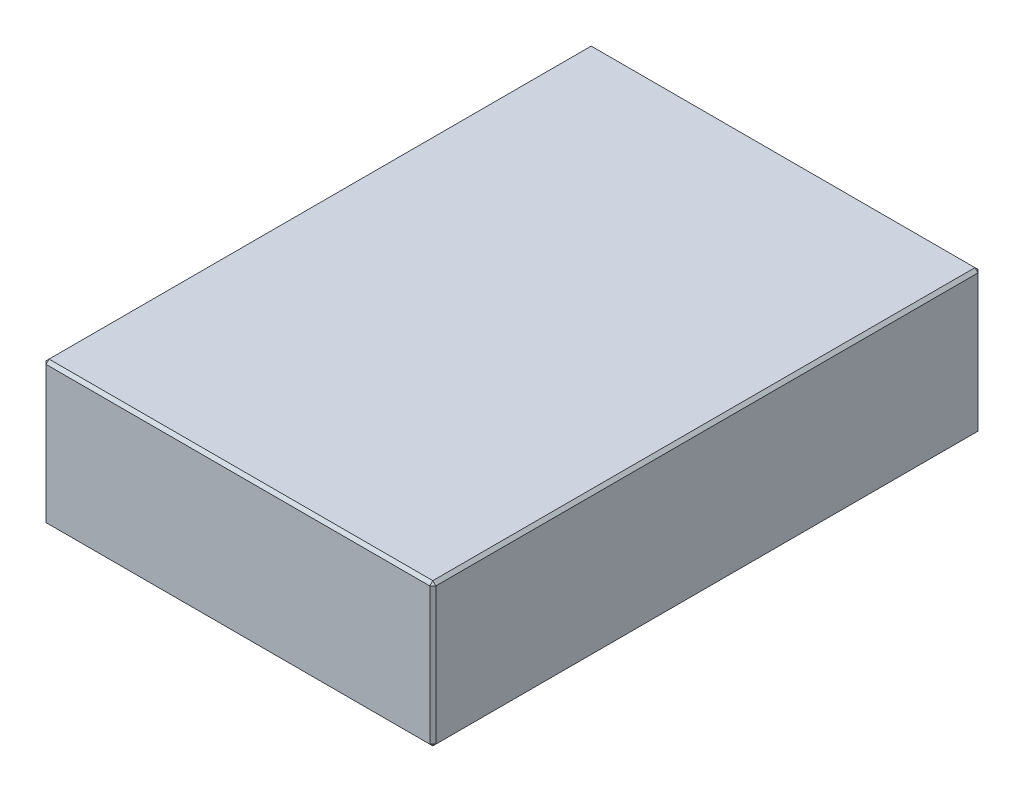
SolidWorks part; units mm, degrees
ref_plane "Front Plane" through (0, 0, 0) normal (0, 0, 1) x (1, 0, 0)
ref_plane "Top Plane" through (0, 0, 0) normal (0, 1, 0) x (1, 0, 0)
ref_plane "Right Plane" through (0, 0, 0) normal (1, 0, 0) x (0, 0, -1)
sketch "Sketch1" plane through (0, 0, 0) normal (0, 1, 0) x (1, 0, 0)
  line L1 (0, 0) -> (64, 0)
  line L2 (0, 0) -> (0, 90)
  line L3 (0, 90) -> (64, 90)
  line L4 (64, 0) -> (64, 90)
  dimension "D1" = 64
  dimension "D2" = 90
extrude "Boss-Extrude1" add sketch "Sketch1" along normal blind 23.5
chamfer "Chamfer1" distance 0.5 angle 45 12 edges at (0, 0, -45) (0, 11.75, -90) (32, 0, -90) (64, 11.75, -90) (64, 0, -45) (0, 11.75, 0) (32, 0, 0) (64, 11.75, 0) (32, 23.5, -90) (64, 23.5, -45) (32, 23.5, 0) (0, 23.5, -45)
